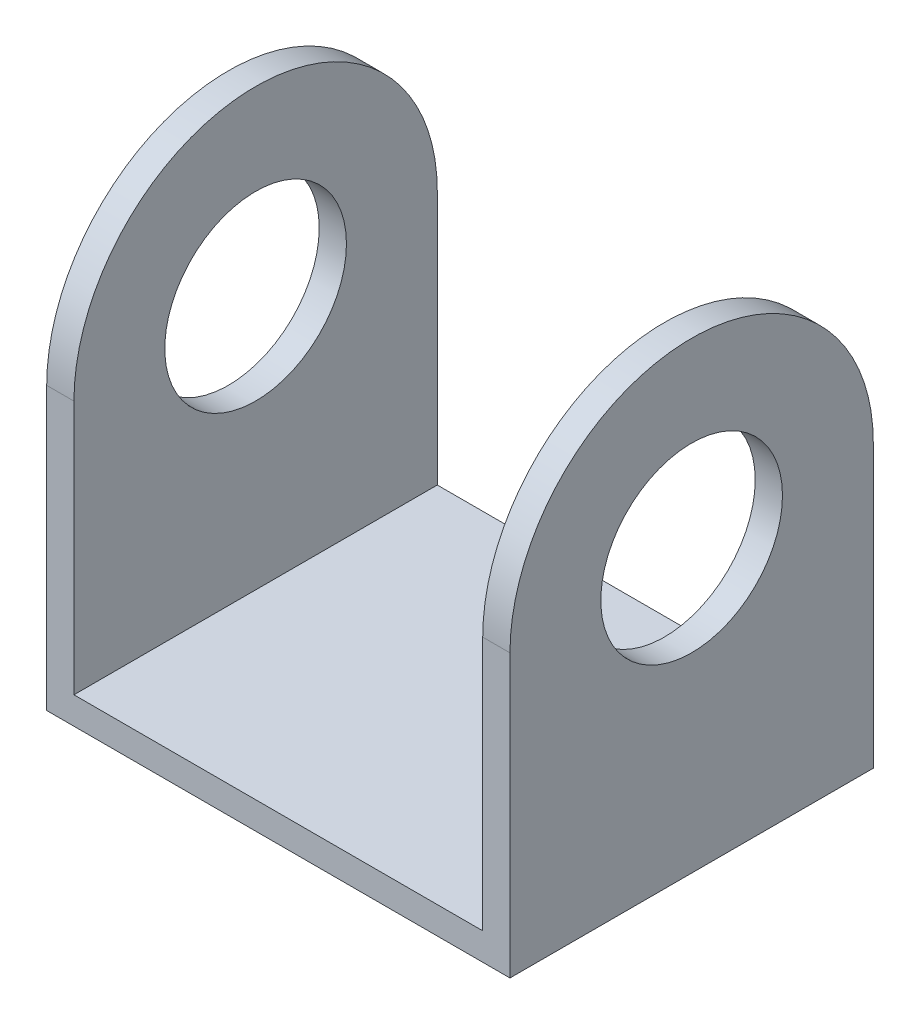
SolidWorks part; units mm, degrees
ref_plane "정면" through (0, 0, 0) normal (0, 0, 1) x (1, 0, 0)
ref_plane "윗면" through (0, 0, 0) normal (0, 1, 0) x (1, 0, 0)
ref_plane "우측면" through (0, 0, 0) normal (1, 0, 0) x (0, 0, -1)
sketch "스케치1" plane through (0, 0, 0) normal (1, 0, 0) x (0, 0, -1)
  line L0 (-20, 0) -> (20, 0)
  line L1 (20, 0) -> (20, 3)
  line L2 (20, 3) -> (-20, 3)
  line L3 (-20, 3) -> (-20, 0)
  point P4 (0, 0)
  dimension "D1" = 40
  dimension "D2" = 3
extrude "보스-돌출1" add sketch "스케치1" along normal mid plane 45
sketch "스케치2" plane through (22.5, 0, 0) normal (1, 0, 0) x (0, 0, -1)
  line L0 (-20, 31) -> (-20, 0)
  line L1 (-20, 0) -> (20, 0)
  line L2 (20, 0) -> (20, 31)
  arc A0 (20, 31) -> (-20, 31) centre (0, 31) ccw
  circle A1 centre (0, 31) radius 10
  dimension "D1" = 31
  dimension "D2" = 20
extrude "보스-돌출2" add sketch "스케치2" along normal blind 3
mirror "대칭 복사1" about plane through (0, 0, 0) normal (1, 0, 0) of "보스-돌출2"
